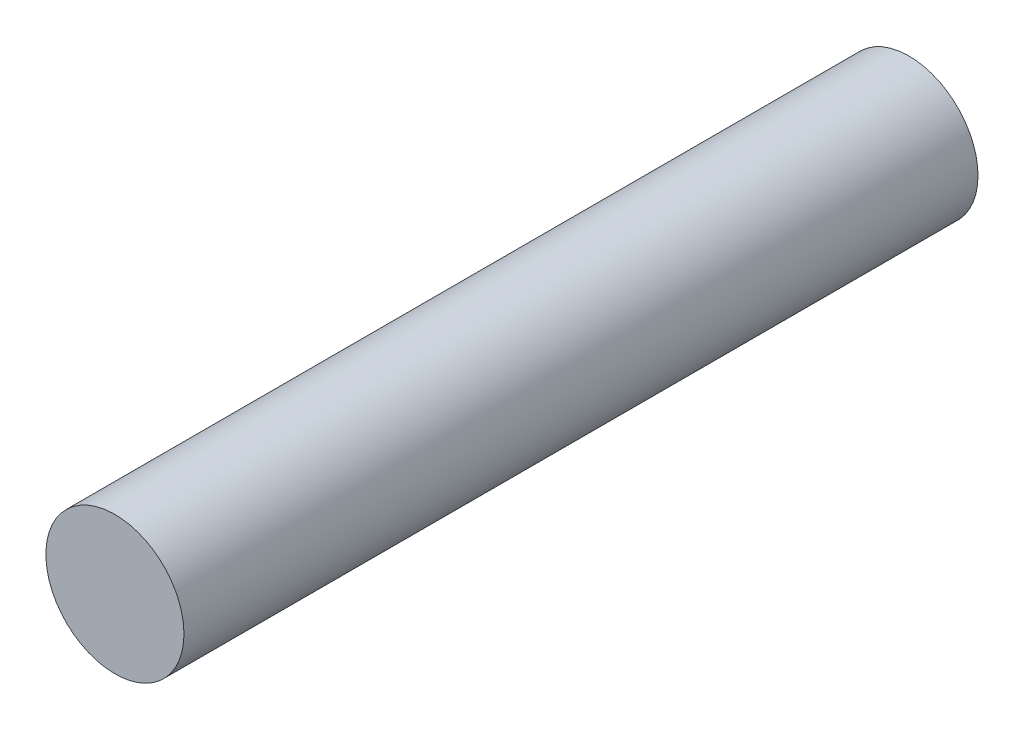
SolidWorks part; units mm, degrees
ref_plane "Front Plane" through (0, 0, 0) normal (0, 0, 1) x (1, 0, 0)
ref_plane "Top Plane" through (0, 0, 0) normal (0, 1, 0) x (1, 0, 0)
ref_plane "Right Plane" through (0, 0, 0) normal (1, 0, 0) x (0, 0, -1)
sketch "Sketch1" plane through (0, 0, 0) normal (0, 0, 1) x (1, 0, 0)
  circle A0 centre (0, 0) radius 4
extrude "Boss-Extrude1" add sketch "Sketch1" along normal blind 46
